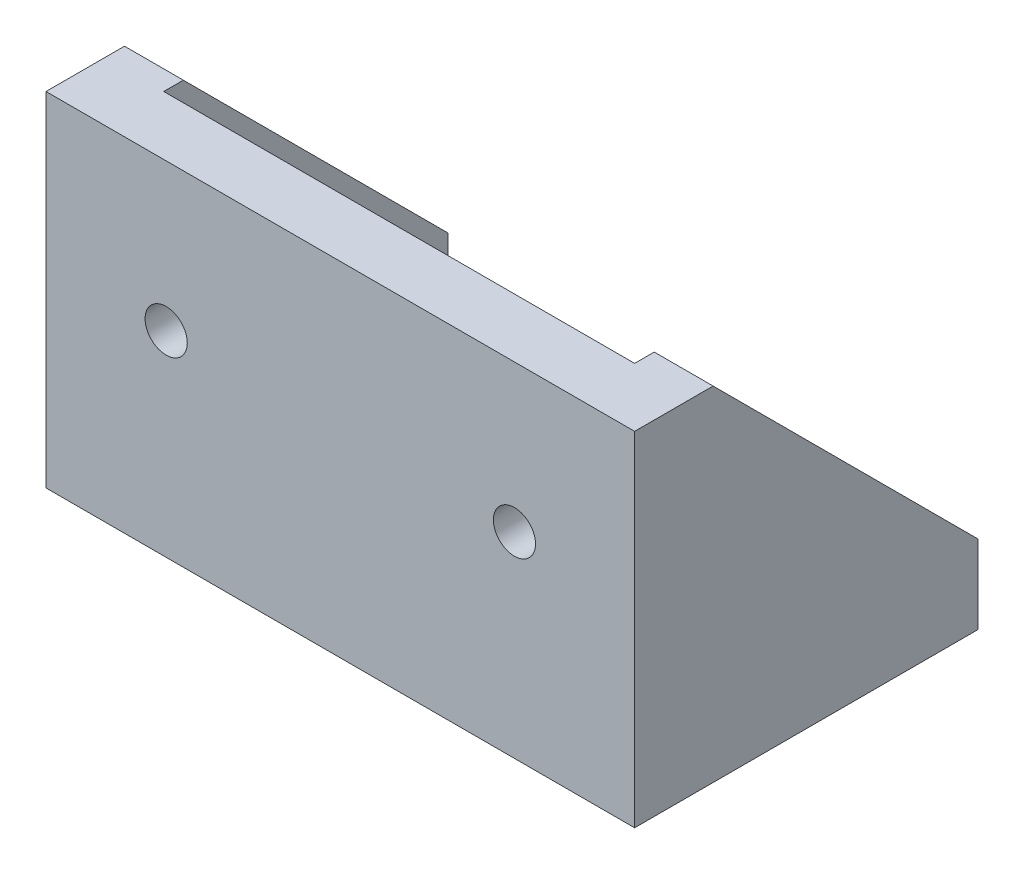
SolidWorks part; units mm, degrees
ref_plane "Front Plane" through (0, 0, 0) normal (0, 0, 1) x (1, 0, 0)
ref_plane "Top Plane" through (0, 0, 0) normal (0, 1, 0) x (1, 0, 0)
ref_plane "Right Plane" through (0, 0, 0) normal (1, 0, 0) x (0, 0, -1)
sketch "Sketch2" plane through (0, 0, 0) normal (1, 0, 0) x (0, 0, -1)
  line L0 (0, 0) -> (35, 0)
  line L1 (35, 0) -> (35, 8)
  line L2 (35, 8) -> (8, 35)
  line L3 (8, 35) -> (0, 35)
  line L4 (0, 35) -> (0, 0)
  dimension "D1" = 8
  dimension "D2" = 8
  dimension "D3" = 35
  dimension "D4" = 35
extrude "Boss-Extrude1" add sketch "Sketch2" along normal mid plane 60 contours L4 L0 L1 L2 L3
ref_point "Point2" parameters "D1"=2
sketch "Sketch5" plane through (0, 0, -35) normal (0, 0, -1) x (-1, 0, 0)
  line L1 (-24, 6) -> (24, 6)
  line L2 (-24, 6) -> (-24, 35)
  line L3 (-24, 35) -> (24, 35)
  line L4 (24, 6) -> (24, 35)
  line L5 (-30, 35) -> (30, 35) construction
  line L6 (-30, 8) -> (-30, 35) construction
  line L7 (30, 8) -> (30, 35) construction
  line L9 (-30, 0) -> (30, 0) construction
  dimension "D1" = 6
  dimension "D2" = 6
  dimension "D3" = 6
extrude "Cut-Extrude1" cut sketch "Sketch5" against normal up to vertex (29 mm away)
sketch "Sketch4" plane through (0, 0, 0) normal (0, 0, 1) x (1, 0, 0)
  line L1 (30, 0) -> (-30, 0) construction
  line L3 (0, -20) -> (0, 40) construction
  circle A0 centre (-17.75, 20) radius 2.15
  circle A1 centre (17.75, 20) radius 2.15
  dimension "D1" = 4.3
  dimension "D2" = 35.5
  dimension "D3" = 20
extrude "Cut-Extrude2" cut sketch "Sketch4" against normal through all
sketch "Sketch6" plane through (0, 6, 0) normal (0, 1, 0) x (1, 0, 0)
  line L0 (-23.1334, 20) -> (14.0091, 20) construction
  line L3 (-24, 6) -> (24, 6) construction
  circle A0 centre (0, 11) radius 3.5
  circle A1 centre (0, 29) radius 3.5
  point P2 (2.2105, 9.561)
  point P3 (-20.9229, 22.7406)
  point P4 (16.2196, 22.5563)
  point P5 (0, 0)
  dimension "D1" = 7
  dimension "D2" = 18
  dimension "D3" = 5
extrude "Cut-Extrude3" cut sketch "Sketch6" against normal through all
